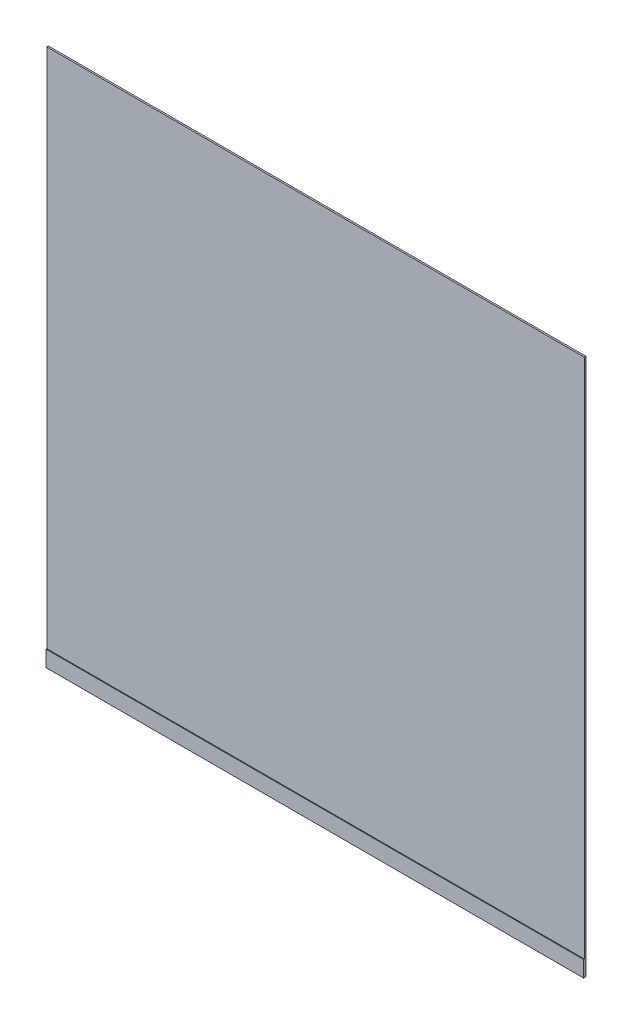
SolidWorks part; units mm, degrees
ref_plane "Front Plane" through (0, 0, 0) normal (0, 0, 1) x (1, 0, 0)
ref_plane "Top Plane" through (0, 0, 0) normal (0, 1, 0) x (1, 0, 0)
ref_plane "Right Plane" through (0, 0, 0) normal (1, 0, 0) x (0, 0, -1)
sketch "Sketch1" plane through (0, 0, 0) normal (0, 0, 1) x (1, 0, 0)
  line L1 (-1750, -1750) -> (1750, -1750)
  line L2 (-1750, -1750) -> (-1750, 1750)
  line L3 (-1750, 1750) -> (1750, 1750)
  line L4 (1750, -1750) -> (1750, 1750)
  line L5 (-1750, -1750) -> (1750, 1750) construction
  line L6 (-1750, 1750) -> (1750, -1750) construction
  point P0 (0, 0)
  dimension "D1" = 3500
  dimension "D2" = 3500
extrude "Boss-Extrude1" add sketch "Sketch1" along normal blind 10
sketch "Sketch2" plane through (0, 0, 10) normal (0, 0, 1) x (1, 0, 0)
  line L0 (1750, -1750) -> (1750, 1750) construction
  line L1 (-1750, -1750) -> (1750, -1750)
  line L2 (-1750, -1750) -> (-1750, -1645.2629)
  line L3 (-1750, -1645.2629) -> (1750, -1645.2629)
  line L4 (1750, -1750) -> (1750, -1645.2629)
extrude "Boss-Extrude2" add sketch "Sketch2" along normal blind 5
